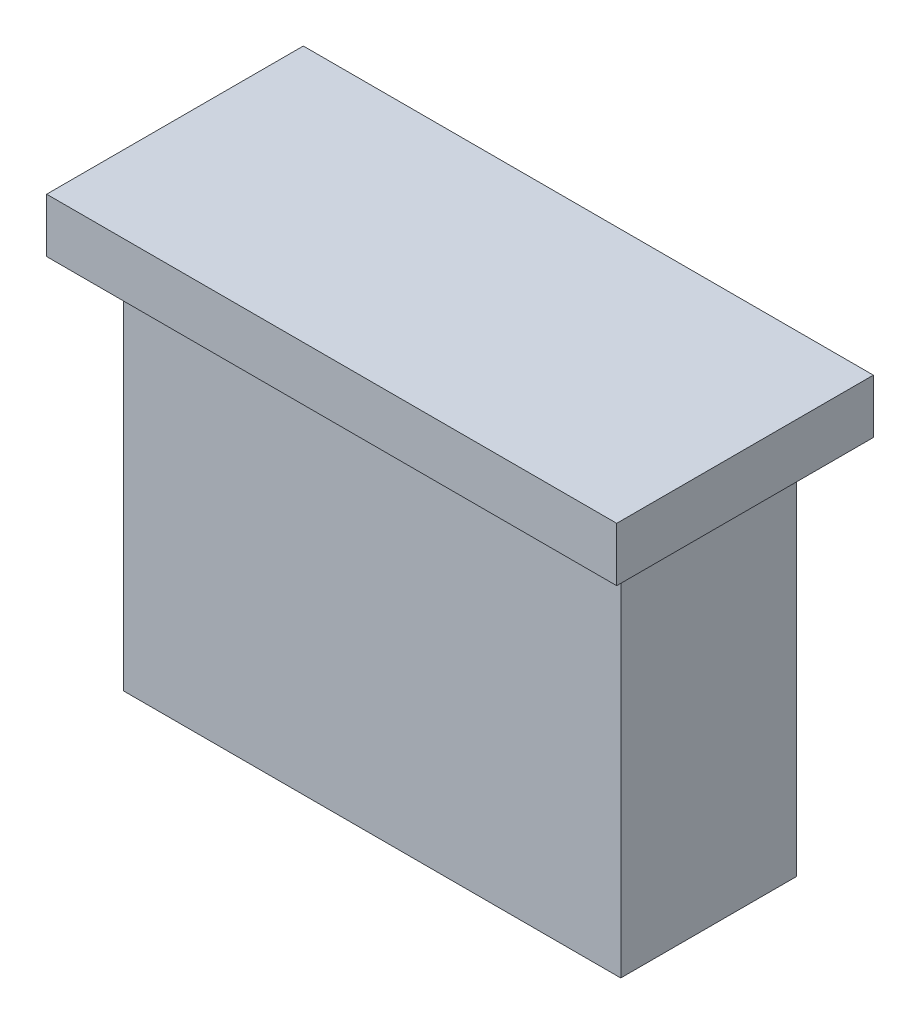
SolidWorks part; units mm, degrees
ref_plane "Front Plane" through (0, 0, 0) normal (0, 0, 1) x (1, 0, 0)
ref_plane "Top Plane" through (0, 0, 0) normal (0, 1, 0) x (1, 0, 0)
ref_plane "Right Plane" through (0, 0, 0) normal (1, 0, 0) x (0, 0, -1)
sketch "Sketch1" plane through (0, 0, 0) normal (0, 1, 0) x (1, 0, 0)
  line L1 (-9.2, -3.25) -> (9.2, -3.25)
  line L2 (-9.2, -3.25) -> (-9.2, 3.25)
  line L3 (-9.2, 3.25) -> (9.2, 3.25)
  line L4 (9.2, -3.25) -> (9.2, 3.25)
  line L5 (-9.2, -3.25) -> (9.2, 3.25) construction
  line L6 (-9.2, 3.25) -> (9.2, -3.25) construction
  point P0 (0, 0)
  dimension "D1" = 18.4
  dimension "D2" = 6.5
extrude "Boss-Extrude1" add sketch "Sketch1" along normal blind 14
sketch "Sketch2" plane through (0, 14, 0) normal (0, 1, 0) x (1, 0, 0)
  line L1 (-10.55, -4.75) -> (10.55, -4.75)
  line L2 (-10.55, -4.75) -> (-10.55, 4.75)
  line L3 (-10.55, 4.75) -> (10.55, 4.75)
  line L4 (10.55, -4.75) -> (10.55, 4.75)
  line L5 (-10.55, -4.75) -> (10.55, 4.75) construction
  line L6 (-10.55, 4.75) -> (10.55, -4.75) construction
  point P0 (0, 0)
  dimension "D1" = 9.5
  dimension "D2" = 21.1
extrude "Boss-Extrude2" add sketch "Sketch2" along normal blind 2
